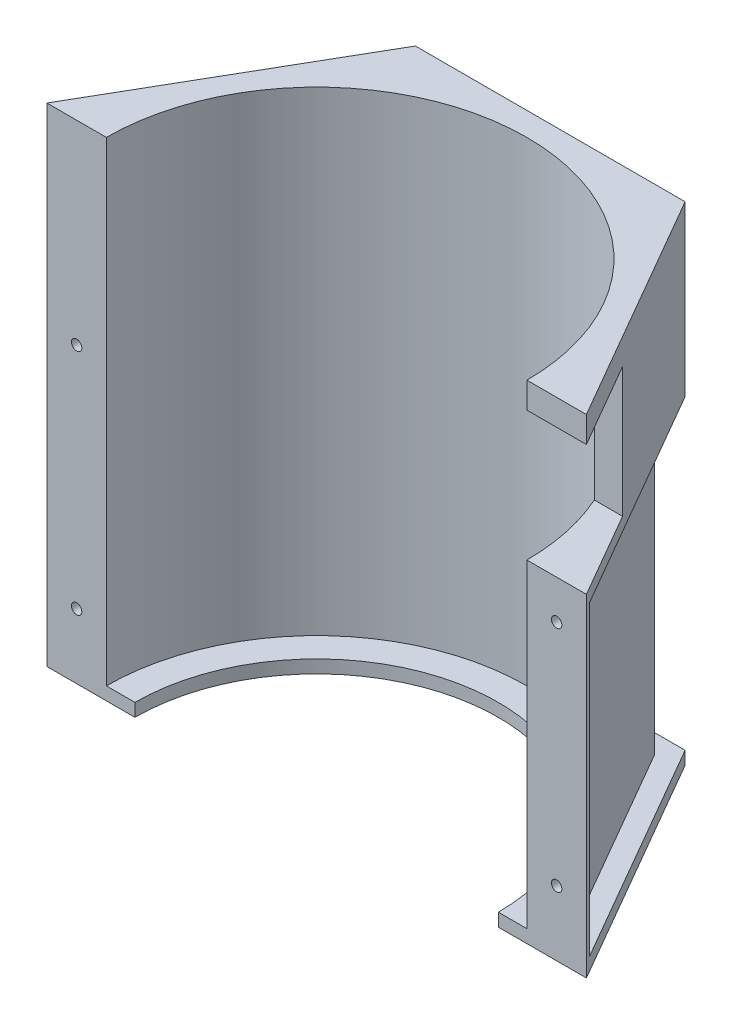
SolidWorks part; units mm, degrees
ref_plane "Front Plane" through (0, 0, 0) normal (0, 0, 1) x (1, 0, 0)
ref_plane "Top Plane" through (0, 0, 0) normal (0, 1, 0) x (1, 0, 0)
ref_plane "Right Plane" through (0, 0, 0) normal (1, 0, 0) x (0, 0, -1)
sketch "Sketch1" plane through (0, 0, 0) normal (0, 1, 0) x (1, 0, 0)
  line L0 (-103.923, 0) -> (-70, 0)
  line L1 (103.923, 0) -> (51.9615, 90)
  line L2 (51.9615, 90) -> (-51.9615, 90)
  line L3 (-51.9615, 90) -> (-103.923, 0)
  line L7 (70, 0) -> (103.923, 0)
  line L8 (51.9615, -90) -> (77.9423, -45) [skipped]
  line L9 (-51.9615, -90) -> (51.9615, -90) [skipped]
  line L10 (-103.923, 0) -> (-77.9423, -45) [skipped]
  arc A0 (70, 0) -> (-70, 0) centre (0, 0) ccw
  arc A2 (90, 0) -> (-90, 0) centre (0, 0) ccw construction
  dimension "D2" = 140
extrude "Boss-Extrude1" add sketch "Sketch1" along normal blind 5
sketch "Sketch2" plane through (0, 5, 0) normal (0, 1, 0) x (1, 0, 0)
  line L0 (-95.2628, 0) -> (-81, 0)
  line L1 (93.5307, 3) -> (47.6314, 82.5)
  line L2 (47.6314, 82.5) -> (-47.6314, 82.5)
  line L3 (-47.6314, 82.5) -> (-93.5307, 3)
  line L7 (81, 0) -> (95.2628, 0)
  line L8 (-71.4471, -41.25) -> (-47.6314, -82.5) [skipped]
  line L9 (-47.6314, -82.5) -> (47.6314, -82.5) [skipped]
  line L10 (71.4471, -41.25) -> (95.2628, 0) [skipped]
  line L11 (95.2628, 0) -> (103.923, 0)
  line L13 (102.191, 3) -> (93.5307, 3)
  line L14 (103.923, 0) -> (102.191, 3)
  line L15 (103.923, 0) -> (51.9615, 90) construction
  line L16 (-95.2628, 0) -> (-103.923, 0)
  line L18 (-102.191, 3) -> (-93.5307, 3)
  line L19 (-103.923, 0) -> (-102.191, 3)
  line L20 (-51.9615, 90) -> (-103.923, 0) construction
  arc A0 (81, 0) -> (-81, 0) centre (0, 0) ccw
  arc A2 (82.5, 0) -> (-82.5, 0) centre (0, 0) ccw construction
  dimension "D1" = 162
extrude "Boss-Extrude2" add sketch "Sketch2" along normal blind 118
sketch "Sketch3" plane through (0, 123, 0) normal (0, 1, 0) x (1, 0, 0)
  line L0 (-103.923, 0) -> (-81, 0)
  line L1 (103.923, 0) -> (51.9615, 90)
  line L2 (51.9615, 90) -> (-51.9615, 90)
  line L3 (-51.9615, 90) -> (-103.923, 0)
  line L7 (81, 0) -> (103.923, 0)
  line L8 (-51.9615, -90) -> (51.9615, -90) [skipped]
  line L9 (-77.9423, -45) -> (-51.9615, -90) [skipped]
  line L10 (77.9423, -45) -> (103.923, 0) [skipped]
  arc A0 (81, 0) -> (-81, 0) centre (0, 0) ccw
  arc A2 (90, 0) -> (-90, 0) centre (0, 0) ccw construction
  dimension "D1" = 162
extrude "Boss-Extrude3" add sketch "Sketch3" along normal blind 5
sketch "Sketch4" plane through (0, 128, 0) normal (0, 1, 0) x (1, 0, 0)
  line L1 (84.8705, 33) -> (73.973, 33)
  line L2 (-103.923, 0) -> (-81, 0)
  line L3 (-103.923, 0) -> (-51.9615, 90)
  line L4 (-51.9615, 90) -> (51.9615, 90)
  line L5 (51.9615, 90) -> (84.8705, 33)
  line L6 (103.923, 0) -> (51.9615, 90) construction
  arc A0 (81, 0) -> (-81, 0) centre (0, 0) ccw construction
  arc A1 (-81, 0) -> (73.973, 33) centre (0, 0) cw
extrude "Boss-Extrude4" add sketch "Sketch4" along normal blind 50
sketch "Sketch5" plane through (0, 178, 0) normal (0, 1, 0) x (1, 0, 0)
  line L0 (-103.923, 0) -> (-51.9615, 90)
  line L1 (-51.9615, 90) -> (51.9615, 90)
  line L2 (51.9615, 90) -> (103.923, 0)
  line L3 (103.923, 0) -> (81, 0)
  line L4 (-103.923, 0) -> (-81, 0)
  arc A0 (-81, 0) -> (81, 0) centre (0, 0) cw
extrude "Boss-Extrude5" add sketch "Sketch5" along normal blind 10
sketch "Sketch6" plane through (0, 0, 0) normal (0, 0, 1) x (1, 0, 0)
  line L0 (92.4615, 128) -> (92.4615, 113)
  line L1 (81, 128) -> (103.923, 128) construction
  line L3 (92.4615, 25) -> (92.4615, 0)
  line L4 (70, 0) -> (103.923, 0) construction
  line L5 (-92.4615, 188) -> (-92.4615, 113)
  line L6 (-103.923, 188) -> (-81, 188) construction
  line L8 (-92.4615, 25) -> (-92.4615, 0)
  line L9 (-103.923, 0) -> (-70, 0) construction
  circle A0 centre (92.4615, 113) radius 2
  circle A1 centre (92.4615, 25) radius 2
  circle A2 centre (-92.4615, 25) radius 2
  circle A3 centre (-92.4615, 113) radius 2
  dimension "D5" = 4
  dimension "D6" = 4
  dimension "D7" = 4
  dimension "D8" = 4
  dimension "D1" = 15
  dimension "D2" = 25
  dimension "D3" = 75
  dimension "D4" = 25
extrude "Cut-Extrude1" cut sketch "Sketch6" against normal blind 10
sketch "Sketch7" plane through (0, 0, 0) normal (0, -1, 0) x (1, 0, 0)
  line L0 (0, -90) -> (0, -85)
  line L1 (51.9615, -90) -> (-51.9615, -90) construction
  line L2 (0, -85) -> (30, -85)
  line L3 (0, -85) -> (-30, -85)
  circle A0 centre (-30, -85) radius 2
  circle A1 centre (30, -85) radius 2
  dimension "D4" = 4
  dimension "D5" = 4
  dimension "D1" = 5
  dimension "D2" = 30
  dimension "D3" = 30
extrude "Cut-Extrude2" cut sketch "Sketch7" against normal blind 10
